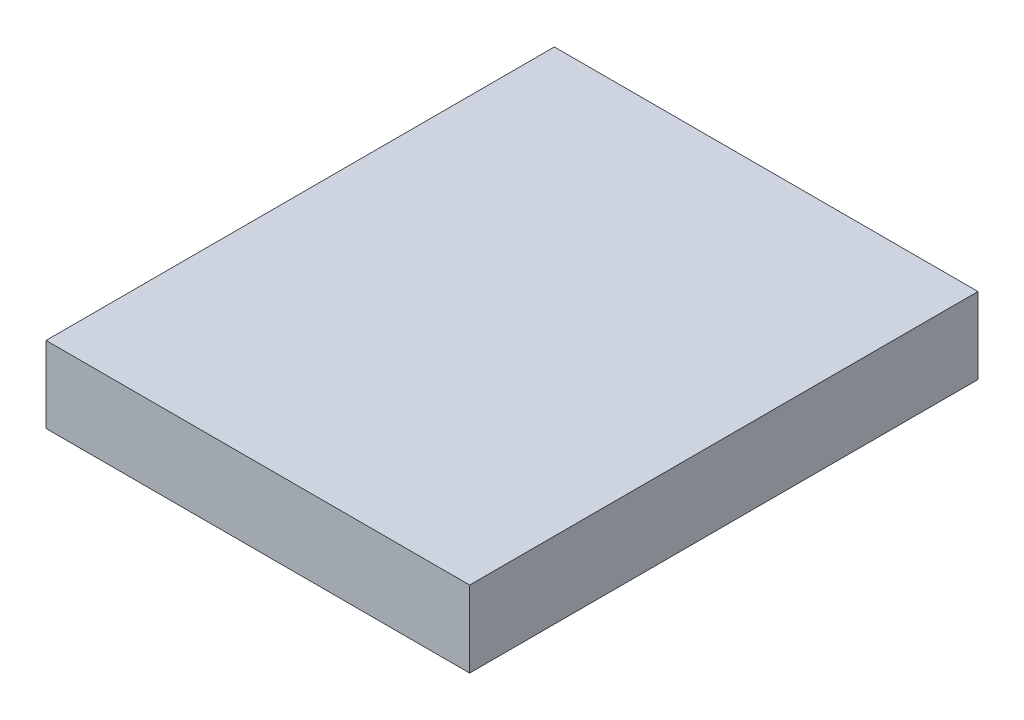
SolidWorks part; units mm, degrees
material "Perspex (TM) GS Acrylic Cast Sheet"
ref_plane "Front Plane" through (0, 0, 0) normal (0, 0, 1) x (1, 0, 0)
ref_plane "Top Plane" through (0, 0, 0) normal (0, 1, 0) x (1, 0, 0)
ref_plane "Right Plane" through (0, 0, 0) normal (1, 0, 0) x (0, 0, -1)
sketch "Sketch1" plane through (0, 0, 0) normal (0, 1, 0) x (1, 0, 0)
  line L1 (-12.5, -15) -> (12.5, -15)
  line L2 (-12.5, -15) -> (-12.5, 15)
  line L3 (-12.5, 15) -> (12.5, 15)
  line L4 (12.5, -15) -> (12.5, 15)
  line L5 (-12.5, -15) -> (12.5, 15) construction
  line L6 (-12.5, 15) -> (12.5, -15) construction
  point P0 (0, 0)
  point P5 (0, 0)
  dimension "D1" = 25
  dimension "D2" = 30
extrude "Boss-Extrude1" add sketch "Sketch1" along normal blind 4.5
